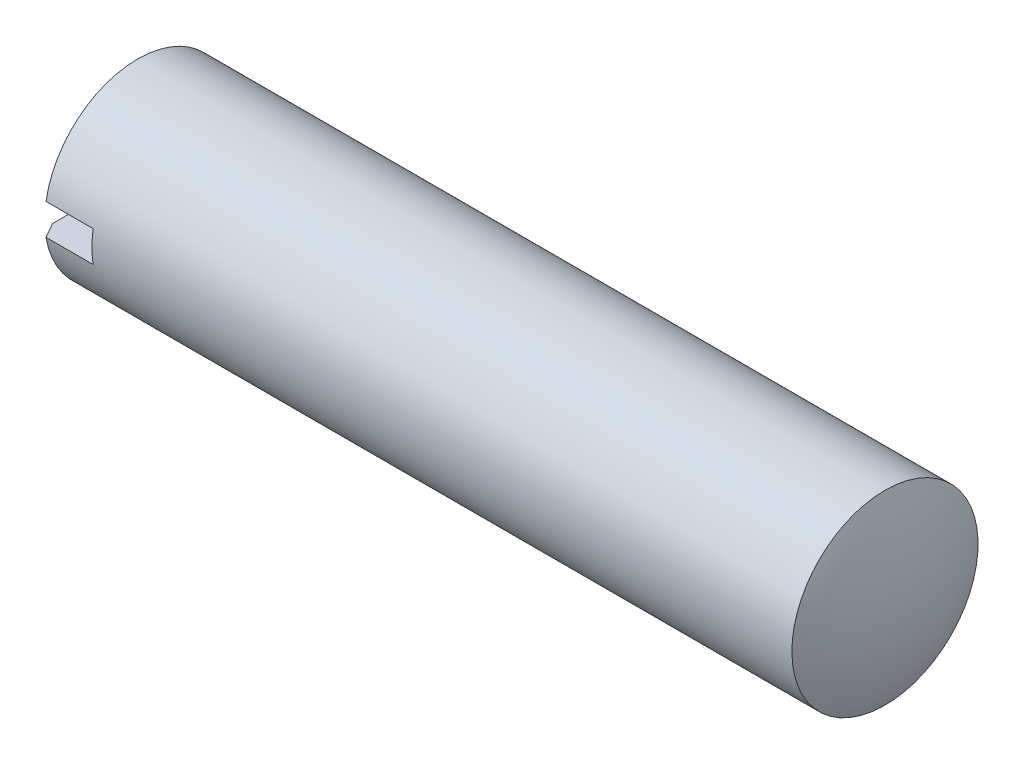
SolidWorks part; units mm, degrees
revolve "BaseBody" add sketch "BodySke"
sketch "BodySke" plane through (0, 0, 0) normal (0, 0, 1) x (1, 0, 0)
  line L0 (0.5566, -6) -> (47.1574, -6) construction
  line L1 (49.1049, 12.7) -> (49.1049, 3.175) construction
  line L2 (0.5566, 6) -> (48.7115, 6)
  line L4 (50, 0) -> (0, 0)
  line L5 (-12.7, 0) -> (88.9, 0) construction
  line L8 (1.75, 12.7) -> (1.75, -3.175) construction
  line L9 (0, 0) -> (0, 5.036)
  line L10 (0, 5.036) -> (0.5566, 6)
  line L11 (0, -5.036) -> (0.5566, -6) construction
  arc A0 (48.7115, 6) -> (50, 0) centre (35.3865, 0) cw
  dimension "Oval_rad" = 14.6135
  dimension "Diameter" = 12
  dimension "Advance" = 1.75
  dimension "Minor_dia" = 10.072
  dimension "Drive_ch_ang" = 60
  dimension "Length" = 50
  dimension "Thread_len" = 48.5483
cosmetic thread "ThreadCosmetic" [suppressed]
extrude "Slot" cut sketch "Sketch2" along normal blind 3.6
sketch "Sketch2" plane through (0, 0, 0) normal (1, 0, 0) x (0, 0, -1)
  line L1 (6, -1) -> (-6, -1)
  line L2 (6, -1) -> (6, 1)
  line L3 (6, 1) -> (-6, 1)
  line L4 (-6, -1) -> (-6, 1)
  dimension "D1" = 12
  dimension "Slot_width" = 2
  dimension "D3" = 6
  dimension "D2" = 1
ref_plane "Plane1" through (0, 0, 0) normal (0, 0, 1) x (1, 0, 0)
ref_plane "Plane2" through (0, 0, 0) normal (0, 1, 0) x (1, 0, 0)
ref_plane "Plane3" through (0, 0, 0) normal (1, 0, 0) x (0, 0, -1)
sketch "ThdSchSke" plane through (0, 0, 0) normal (0, 0, 1) x (1, 0, 0)
  line L0 (0.5566, -5.036) -> (-0.1184, -6)
  line L1 (0.5566, -5.036) -> (1.2316, -6)
  line L2 (1.2316, -6) -> (1.2316, -7.5)
  line L3 (-3.175, 0) -> (5.1513, 0) construction
  line L5 (1.2316, -7.5) -> (-0.1184, -7.5)
  line L6 (-0.1184, -7.5) -> (-0.1184, -6)
  line L7 (0.5566, -6) -> (0.5566, -1) construction
  dimension "Diameter" = 12
  dimension "Thread_minor" = 10.072
revolve "ThreadSchematic" [suppressed] cut sketch "ThdSchSke" angle 360 about L3
pattern_linear "ThdSchPat" [suppressed]
equation "\"D1@Sketch2\" = \"Diameter@BodySke\""
equation "\"D3@Sketch2\" = \"D1@Sketch2\" / 2"
equation "\"D2@Sketch2\" = \"Slot_width@Sketch2\" / 2"
equation "\"Thread_minor@ThdSchSke\" = \"Minor_dia@BodySke\""
equation "\"Diameter@ThdSchSke\" = \"Diameter@BodySke\""
equation "\"Overcut@ThdSchSke\" = \"Diameter@BodySke\" * 1.25"
equation "' \"Num_threads@ThdSchPat\" = int( (\"Length@BodySke\" - ( ( ( \"Diameter@BodySke\" - \"Minor_dia@BodySke\" ) * 0.5 ) / tan( \"Drive_ch_ang@BodySke\" * 0.017453292 ) ) - ( ( ( \"Diameter@BodySke\" - \"Cup_dia@BodySke\" ) * 0.5 ) * tan( \"Nose_ch_ang@BodySke\" * 0.017453292 ) ) ) / \"Advance@BodySke\" + 0.999 )  + 1"
equation "' \"Advance@ThdSchPat\" = (\"Length@BodySke\" - ( ( ( \"Diameter@BodySke\" - \"Minor_dia@BodySke\" ) * 0.5 ) / tan( \"Drive_ch_ang@BodySke\" * 0.017453292 ) ) - ( ( ( \"Diameter@BodySke\" - \"Cup_dia@BodySke\" ) * 0.5 ) * tan( \"Nose_ch_ang@BodySke\" * 0.017453292 ) ) ) /  (\"Num_threads@ThdSchPat\" - 1) 'relax it"
equation "' \"Num_threads@ThdSchPat\" = \"Num_threads@ThdSchPat\" - sgn( \"Num_threads@ThdSchPat\" - 1) '---chamfered tips only---"
equation "\"Thread_len@BodySke\" = \"Length@BodySke\" -  ( ( ( \"Diameter@BodySke\" - \"Minor_dia@BodySke\" ) * 0.5 ) / tan( \"Drive_ch_ang@BodySke\" * 0.017453292 ) )"
equation "\"Thread_len@BodySke\" = \"Thread_len@BodySke\" - \"Oval_rad@BodySke\" + sqr(\"Oval_rad@BodySke\" * \"Oval_rad@BodySke\" - (\"Minor_dia@BodySke\" / 2) * (\"Minor_dia@BodySke\" / 2))"
equation "\"Num_threads@ThdSchPat\" = int( \"Thread_len@BodySke\" / \"Advance@BodySke\" + 0.999 ) + 1"
equation "\"Advance@ThdSchPat\" = \"Thread_len@BodySke\" /  (\"Num_threads@ThdSchPat\" - 1)"
